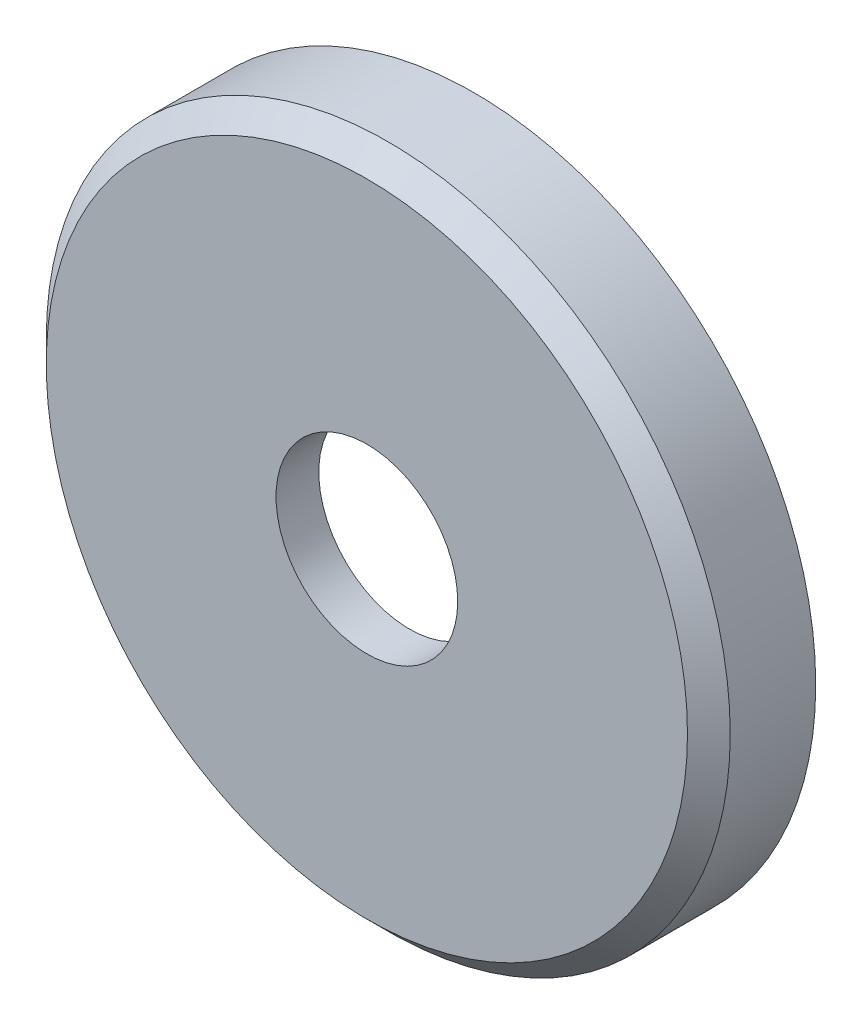
SolidWorks part; units mm, degrees
ref_plane "Plano frontal" through (0, 0, 0) normal (0, 0, 1) x (1, 0, 0)
ref_plane "Plano superior" through (0, 0, 0) normal (0, 1, 0) x (1, 0, 0)
ref_plane "Plano direito" through (0, 0, 0) normal (1, 0, 0) x (0, 0, -1)
sketch "Sketch1" plane through (0, 0, 0) normal (0, 0, 1) x (1, 0, 0)
  circle A0 centre (0, 0) radius 12.5
  circle A1 centre (0, 0) radius 16
  dimension "D1" = 25
  dimension "D2" = 32
extrude "Boss-Extrude1" add sketch "Sketch1" along normal blind 3
sketch "Sketch2" plane through (0, 0, 3) normal (0, 0, 1) x (1, 0, 0)
  circle A1 centre (0, 0) radius 16
  circle A2 centre (0, 0) radius 16
  circle A3 centre (0, 0) radius 4.25
  dimension "D2" = 8.5
  dimension "D1" = 0
extrude "Boss-Extrude2" add sketch "Sketch2" along normal blind 2
chamfer "Chamfer1" distance 1 angle 45 1 edges at (16, 0, 5)
ref_point "Point1"
ref_point "Point2"
ref_point "Point3"
